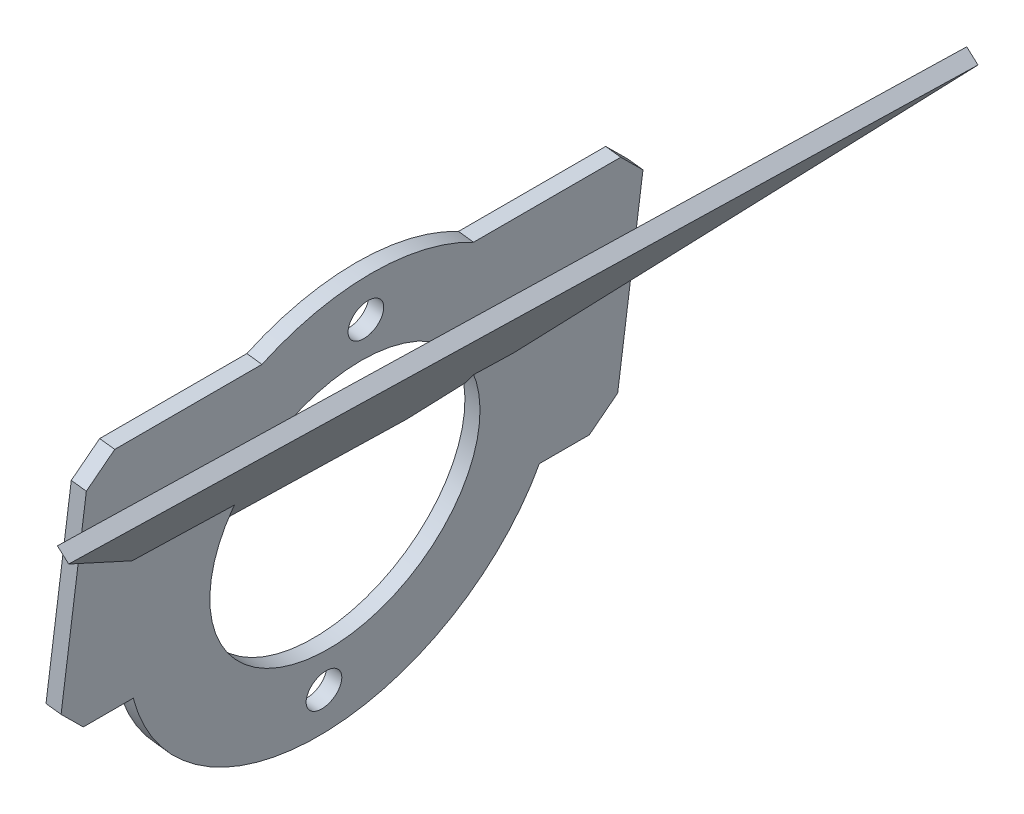
SolidWorks part; units mm, degrees
ref_plane "Front Plane" through (0, 0, 0) normal (0, 0, 1) x (1, 0, 0)
ref_plane "Top Plane" through (0, 0, 0) normal (0, 1, 0) x (1, 0, 0)
ref_plane "Right Plane" through (0, 0, 0) normal (1, 0, 0) x (0, 0, -1)
sketch3d "3DSketch2"
  line L1 (611.6867, 563.7649, 0) -> (934.5194, 524.126, 0) construction
  line L2 (776.8006, 646.6782, -180.744) -> (670.48, 558.1547, -31.8084) construction
  line L3 (761.0423, 669.4594, 164.2185) -> (670.7309, 560.198, 32.3601) construction
  spline S2 degree 3 poles (672.292, 572.9123, -47.9154) (670.9181, 561.7223, -54.5867) (669.0877, 546.815, -29.2052) (670.4616, 558.005, -22.5339) (671.8356, 569.195, -15.8626) (673.666, 584.1023, -41.2441) (672.292, 572.9123, -47.9154) (670.9181, 561.7223, -54.5867) (669.0877, 546.815, -29.2052) knots -0.5 0 0 0 0.5 0.5 0.5 1 1 1 1.5 1.5 1.5 weights 1 0.333333 0.333333 1 0.333333 0.333333 1 0.333333 0.333333 only from (672.292, 572.9123, -47.9154) to (672.292, 572.9123, -47.9154) construction
ref_plane "Plane1" through (111.3143, -95.1392, 2.5944) normal (0.7601, -0.6496, 0.0177) x (0.0131, -0.012, -0.9998)
ref_plane "Plane2" through (117.3568, -100.3037, 2.7352) normal (0.7601, -0.6496, 0.0177) x (0.0131, -0.012, -0.9998)
sketch "Sketch2" plane through (117.3568, -100.3037, 2.7352) normal (0.7601, -0.6496, 0.0177) x (0.0131, -0.012, -0.9998)
  line L0 (-30.2783, 861.6166) -> (-81.5144, 916.6166)
  line L1 (-162.241, 1003.2736) -> (-30.2783, 861.6166) construction
  line L2 (-81.5144, 916.6166) -> (95.8899, 916.6166)
  line L3 (183.1459, 996.3978) -> (33.9012, 859.9381) construction
  line L4 (95.8899, 916.6166) -> (19.7526, 861.6166)
  line L5 (19.7526, 861.6166) -> (-30.2783, 861.6166)
  dimension "D1" = 55
extrude "Boss-Extrude1" add sketch "Sketch2" against normal blind 3 from offset 15.9 offset against normal yes
ref_plane "Plane4" through (611.6867, 563.7649, 0) normal (0.9925, -0.1219, 0) x (0, 0, -1)
ref_plane "Plane3" through (593.007, -72.8121, 0) normal (0.9925, -0.1219, 0) x (0, 0, -1)
ref_plane "Plane5" through (590.0294, -72.4465, 0) normal (0.9925, -0.1219, 0) x (0, 0, -1)
sketch "Sketch3" plane through (590.0294, -72.4465, 0) normal (0.9925, -0.1219, 0) x (0, 0, -1)
  line L0 (0, 681.8946) -> (0, 596.8946) construction
  line L20 (40.1279, 625.3946) -> (50, 625.3946)
  line L21 (50, 625.3946) -> (55, 630.3946)
  line L22 (55, 630.3946) -> (55, 671.3946)
  line L23 (55, 671.3946) -> (50, 676.3946)
  line L24 (50, 676.3946) -> (20.9105, 676.3946)
  line L25 (-20.9105, 676.3946) -> (-50, 676.3946)
  line L26 (-50, 676.3946) -> (-55, 671.3946)
  line L27 (-55, 671.3946) -> (-55, 630.3946)
  line L28 (-55, 630.3946) -> (-50, 625.3946)
  line L29 (-50, 625.3946) -> (-40.1279, 625.3946)
  circle A1 centre (0, 639.3946) radius 26.5 construction
  arc A4 (20.9105, 676.3946) -> (-20.9105, 676.3946) centre (0, 639.3946) ccw
  arc A5 (-40.1279, 625.3946) -> (40.1279, 625.3946) centre (0, 639.3946) ccw
  circle A7 centre (0, 605.3946) radius 3.5
  circle A8 centre (0, 673.3946) radius 3.5
  circle A9 centre (0, 639.3946) radius 26.5
  ellipse E0 centre (0, 605.4319) end of major axis (3.5, 605.4319) minor radius 3.4979 construction
  ellipse E1 centre (0, 673.3904) end of major axis (3.5, 673.3904) minor radius 3.4979 construction
  ellipse E2 centre (0, 605.4319) end of major axis (3.5, 605.4319) minor radius 3.4979 construction
  ellipse E3 centre (0, 673.3904) end of major axis (3.5, 673.3904) minor radius 3.4979 construction
  point P11 (0, 639.3946)
extrude "Boss-Extrude2" add sketch "Sketch3" along normal blind 3 separate body contours A9
